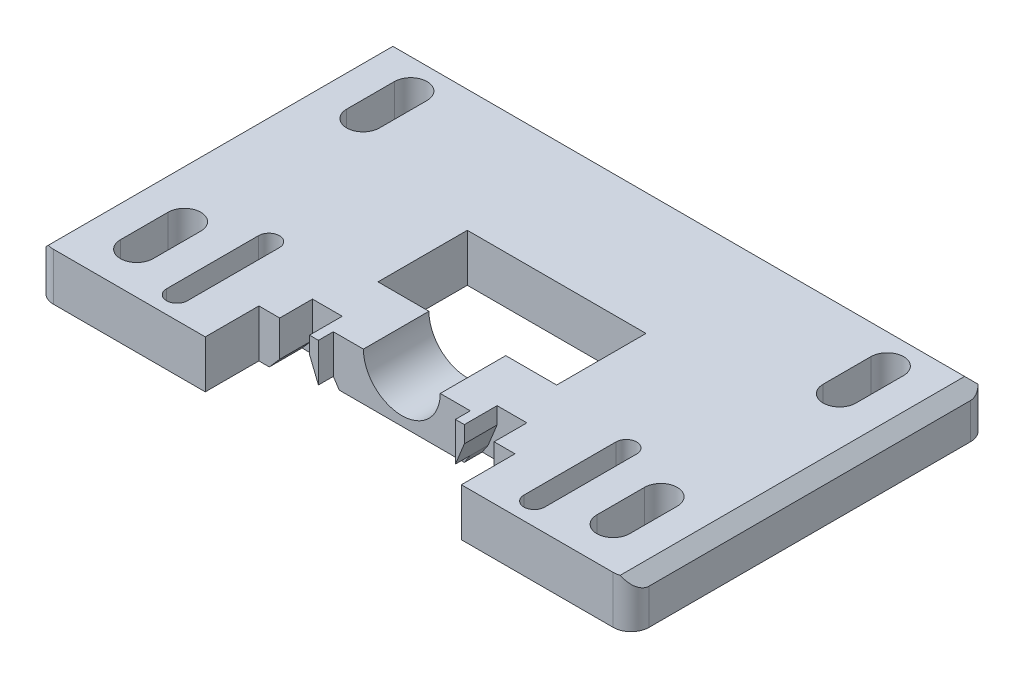
SolidWorks part; units mm, degrees
ref_plane "Front Plane" through (0, 0, 0) normal (0, 0, 1) x (1, 0, 0)
ref_plane "Top Plane" through (0, 0, 0) normal (0, 1, 0) x (1, 0, 0)
ref_plane "Right Plane" through (0, 0, 0) normal (1, 0, 0) x (0, 0, -1)
sketch "Sketch1" plane through (0, 0, 0) normal (0, 1, 0) x (1, 0, 0)
  line L0 (40, 23) -> (40, 15) construction
  line L1 (-50, 30) -> (50, 30)
  line L2 (-50, 30) -> (-50, -30)
  line L3 (-50, -30) -> (50, -30)
  line L4 (50, 30) -> (50, -30)
  line L5 (-15, -7.5) -> (15, -7.5)
  line L6 (-15, -7.5) -> (-15, 7.5)
  line L7 (-15, 7.5) -> (15, 7.5)
  line L8 (15, -7.5) -> (15, 7.5)
  line L9 (-15, -7.5) -> (15, 7.5) construction
  line L10 (-15, 7.5) -> (15, -7.5) construction
  line L11 (42.75, 23) -> (42.75, 15)
  line L12 (37.25, 23) -> (37.25, 15)
  line L13 (40, -23) -> (40, -15) construction
  line L14 (37.25, -23) -> (37.25, -15)
  line L15 (42.75, -23) -> (42.75, -15)
  line L16 (-40, -15) -> (-40, -23) construction
  line L17 (-37.25, -15) -> (-37.25, -23)
  line L18 (-42.75, -15) -> (-42.75, -23)
  line L19 (-40, 23) -> (-40, 15) construction
  line L20 (-37.25, 23) -> (-37.25, 15)
  line L21 (-42.75, 23) -> (-42.75, 15)
  line L22 (-30, -26.25) -> (-30, -10.81) construction
  line L23 (-21.5, -30) -> (21.5, -30)
  line L24 (-21.5, -30) -> (-21.5, -21)
  line L25 (-21.5, -21) -> (21.5, -21)
  line L26 (21.5, -30) -> (21.5, -21)
  line L27 (11.5, -21) -> (-11.5, -21)
  line L28 (11.5, -21) -> (11.5, -18.5)
  line L29 (11.5, -18.5) -> (-11.5, -18.5)
  line L30 (-11.5, -21) -> (-11.5, -18.5)
  line L31 (-31.75, -26.25) -> (-31.75, -10.81)
  line L32 (-28.25, -26.25) -> (-28.25, -10.81)
  line L33 (30, -10.81) -> (30, -26.25) construction
  line L34 (31.75, -10.81) -> (31.75, -26.25)
  line L35 (28.25, -10.81) -> (28.25, -26.25)
  line L37 (13, -21) -> (18, -21)
  line L38 (13, -21) -> (13, -15.5)
  line L39 (13, -15.5) -> (18, -15.5)
  line L40 (18, -21) -> (18, -15.5)
  line L41 (-13, -21) -> (-18, -21)
  line L42 (-13, -21) -> (-13, -15.5)
  line L43 (-13, -15.5) -> (-18, -15.5)
  line L44 (-18, -21) -> (-18, -15.5)
  circle A0 centre (-40, 19) radius 2.75
  circle A1 centre (-40, 19) radius 11.95 construction
  circle A2 centre (40, 19) radius 2.75
  circle A3 centre (-40, -19) radius 2.75
  circle A4 centre (40, -19) radius 2.75
  arc A5 (42.75, 23) -> (37.25, 23) centre (40, 23) ccw
  arc A6 (37.25, 15) -> (42.75, 15) centre (40, 15) ccw
  arc A7 (37.25, -23) -> (42.75, -23) centre (40, -23) ccw
  arc A8 (42.75, -15) -> (37.25, -15) centre (40, -15) ccw
  arc A9 (-37.25, -15) -> (-42.75, -15) centre (-40, -15) ccw
  arc A10 (-42.75, -23) -> (-37.25, -23) centre (-40, -23) ccw
  arc A11 (-37.25, 23) -> (-42.75, 23) centre (-40, 23) ccw
  arc A12 (-42.75, 15) -> (-37.25, 15) centre (-40, 15) ccw
  arc A13 (-31.75, -26.25) -> (-28.25, -26.25) centre (-30, -26.25) ccw
  arc A14 (-28.25, -10.81) -> (-31.75, -10.81) centre (-30, -10.81) ccw
  arc A15 (31.75, -10.81) -> (28.25, -10.81) centre (30, -10.81) ccw
  arc A16 (28.25, -26.25) -> (31.75, -26.25) centre (30, -26.25) ccw
  point P14 (0, 0)
  point P21 (40, 19)
  point P28 (40, -19)
  point P35 (-40, -19)
  point P42 (-40, 19)
  point P51 (0, -21)
  point P56 (0, -18.5)
  point P59 (-30, -18.53)
  point P66 (30, -18.53)
  dimension "D5" = 5.5
  dimension "D8" = 23.9
  dimension "D9" = 5.5
  dimension "D10" = 10
  dimension "D12" = 5.5
  dimension "D13" = 11
  dimension "D14" = 10
  dimension "D15" = 11
  dimension "D16" = 5.5
  dimension "D33" = 10
  dimension "D1" = 60
  dimension "D2" = 100
  dimension "D3" = 50
  dimension "D4" = 30
  dimension "D6" = 10
  dimension "D7" = 11
  dimension "D11" = 11
  dimension "10" = 10
  dimension "D17" = 15
  dimension "D18" = 30
  dimension "D19" = 5.5
  dimension "D20" = 8
  dimension "D21" = 5.5
  dimension "D22" = 8
  dimension "D23" = 5.5
  dimension "D24" = 8
  dimension "D25" = 5.5
  dimension "D26" = 8
  dimension "D27" = 43
  dimension "D28" = 9
  dimension "D29" = 2.5
  dimension "D30" = 23
  dimension "D31" = 3.5
  dimension "D32" = 15.44
  dimension "D34" = 3.75
  dimension "D35" = 3.5
  dimension "D36" = 15.44
  dimension "D37" = 10
  dimension "D38" = 3.75
  dimension "D39" = 13
  dimension "D40" = 5
  dimension "D41" = 5.5
  dimension "D42" = 5
  dimension "D43" = 13
  dimension "D44" = 5.5
sketch "Sketch2" plane through (0, 0, 0) normal (0, 1, 0) x (1, 0, 0)
  line L0 (-100, -10) -> (100, 10) construction
  line L1 (-100, 10) -> (100, 10) construction
  line L2 (-100, 10) -> (-100, -10) construction
  line L3 (-100, -10) -> (100, -10) construction
  line L4 (100, 10) -> (100, -10) construction
  dimension "D1" = 200
  dimension "D2" = 20
extrude "Boss-Extrude1" add sketch "Sketch1" along normal blind 8 contours L4 L1 L2 L3 A12 L21 A11 L20 A10 L18 A9 L17 A8 L15 A7 L14 A6 L12 A5 L11 L8 L5 L6 L7
sketch "Sketch4" plane through (0, 0, 18.5) normal (0, 0, 1) x (1, 0, 0)
  line L0 (11.5, 8) -> (-11.5, 8) construction
  circle A0 centre (0, 8) radius 6.45
  dimension "D1" = 12.9
extrude "Cut-Extrude1" cut sketch "Sketch4" against normal up to surface (11 mm away) up to face at (0, 4, 7.5)
sketch "Sketch5" plane through (0, 0, 21) normal (0, 0, 1) x (1, 0, 0)
  line L0 (13, 5.2) -> (11.5, 1.5)
  line L2 (11.5, 8) -> (11.5, 0) construction
  line L3 (18, 2) -> (19.75, 0)
  line L4 (18, 8) -> (18, 0) construction
  line L5 (18, 0) -> (21.5, 0) construction
  line L6 (21.5, 0) -> (21.5, 8) construction
  line L7 (21.5, 8) -> (18, 8) construction
  line L8 (11.5, 0) -> (13, 0) construction
  line L9 (13, 0) -> (13, 8) construction
  line L10 (13, 8) -> (11.5, 8) construction
  line L11 (18, 0) -> (21.5, 0)
  line L12 (21.5, 0) -> (21.5, 8)
  line L13 (21.5, 8) -> (18, 8)
  line L14 (18, 8) -> (18, 0)
  line L15 (11.5, 0) -> (13, 0)
  line L16 (13, 0) -> (13, 8)
  line L17 (13, 8) -> (11.5, 8)
  line L18 (11.5, 8) -> (11.5, 0)
  line L19 (13, 8) -> (13, 0) construction
  line L21 (-21.5, 0) -> (-18, 0) construction
  line L22 (-18, 0) -> (-18, 8) construction
  line L23 (-18, 8) -> (-21.5, 8) construction
  line L24 (-21.5, 8) -> (-21.5, 0) construction
  line L25 (-13, 0) -> (-11.5, 0) construction
  line L26 (-11.5, 0) -> (-11.5, 8) construction
  line L27 (-11.5, 8) -> (-13, 8) construction
  line L28 (-13, 8) -> (-13, 0) construction
  line L29 (-21.5, 0) -> (-18, 0)
  line L30 (-18, 0) -> (-18, 8)
  line L31 (-18, 8) -> (-21.5, 8)
  line L32 (-21.5, 8) -> (-21.5, 0)
  line L33 (-13, 0) -> (-11.5, 0)
  line L34 (-11.5, 0) -> (-11.5, 8)
  line L35 (-11.5, 8) -> (-13, 8)
  line L36 (-13, 8) -> (-13, 0)
  line L37 (-13, 5.2) -> (-11.5, 1.5)
  line L38 (-18, 2) -> (-19.75, 0)
  line L39 (11.5, 1.5) -> (10.5, 0)
  line L40 (-11.5, 1.5) -> (-10.5, 0)
  line L44 (-6.45, 8) -> (-11.5, 8)
  line L45 (-11.5, 8) -> (-11.5, 0)
  line L46 (-11.5, 0) -> (11.5, 0)
  line L47 (11.5, 0) -> (11.5, 8)
  line L48 (11.5, 8) -> (6.45, 8)
  line L49 (-6.45, 8) -> (-11.5, 8)
  line L50 (-11.5, 8) -> (-11.5, 0)
  line L51 (-11.5, 0) -> (11.5, 0)
  line L52 (11.5, 0) -> (11.5, 8)
  line L53 (11.5, 8) -> (6.45, 8)
  arc A1 (-6.45, 8) -> (6.45, 8) centre (0, 8) ccw
  arc A2 (-6.45, 8) -> (6.45, 8) centre (0, 8) ccw
  line M1 (18, 0) -> (21.5, 0)
  line M4 (18, 8) -> (18, 0)
  dimension "D1" = 1.5
  dimension "D2" = 2
  dimension "D3" = 5.2
  dimension "D4" = 5.2
  dimension "D5" = 1.5
  dimension "D6" = 2
  dimension "D8" = 1
  dimension "D9" = 1
  dimension "D7" = 0
extrude "Cut-Extrude2" cut sketch "Sketch5" against normal up to surface (5.5 mm away) contours L0 L18 L15 L16 | L3 M4 M1 | L37 L36 L33 L34 | L30 L38 L29 | L39 L51 L18 | L34 L51 L40 up to face at (15.5, 4, 15.5)
chamfer "Chamfer1" distance 2 angle 45 3 edges at (50, 8, 0) (0, 8, -30) (-50, 8, 0)
fillet "Fillet1" radius 3 4 edges at (-50, 3, 30) (50, 3, 30) (50, 3, -30) (-50, 3, -30)
